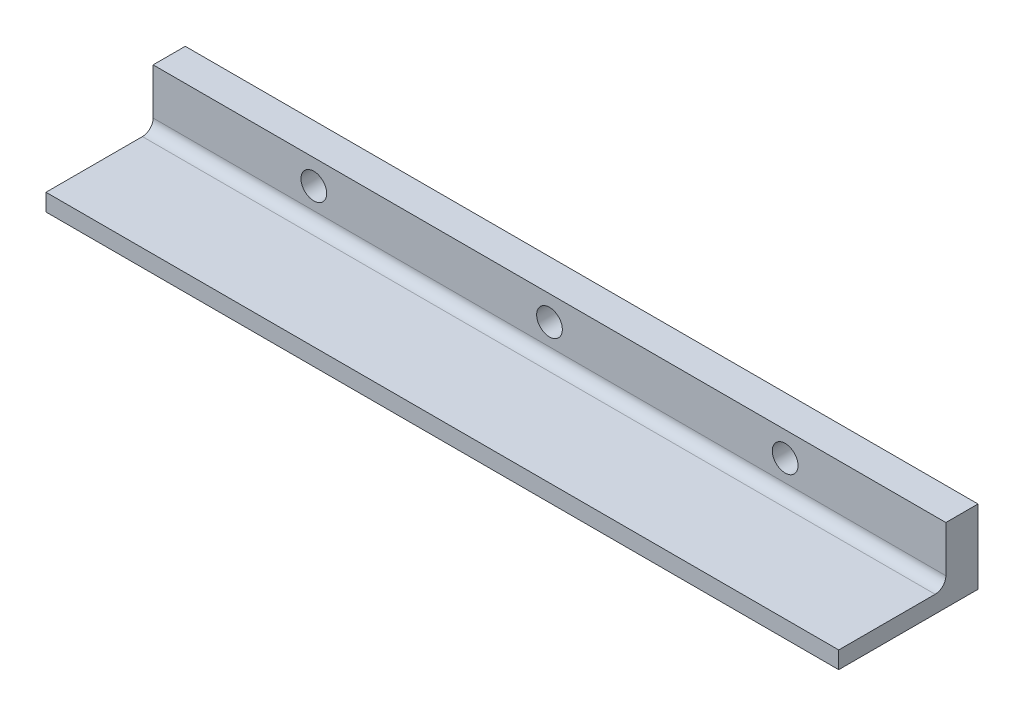
SolidWorks part; units mm, degrees
ref_plane "Front Plane" through (0, 0, 0) normal (0, 0, 1) x (1, 0, 0)
ref_plane "Top Plane" through (0, 0, 0) normal (0, 1, 0) x (1, 0, 0)
ref_plane "Right Plane" through (0, 0, 0) normal (1, 0, 0) x (0, 0, -1)
sketch "Sketch1" plane through (0, 0, 0) normal (0, 1, 0) x (1, 0, 0)
  line L1 (-37, -6.5) -> (37, -6.5)
  line L2 (-37, -6.5) -> (-37, 6.5)
  line L3 (-37, 6.5) -> (37, 6.5)
  line L4 (37, -6.5) -> (37, 6.5)
  line L5 (-37, -6.5) -> (37, 6.5) construction
  line L6 (-37, 6.5) -> (37, -6.5) construction
  point P0 (0, 0)
  dimension "D1" = 13
  dimension "D2" = 74
extrude "Boss-Extrude1" add sketch "Sketch1" along normal blind 1.6
sketch "Sketch2" plane through (0, 1.6, 0) normal (0, 1, 0) x (1, 0, 0)
  line L0 (37, -6.5) -> (37, 6.5) construction
  line L1 (-37, 6.5) -> (37, 6.5)
  line L2 (-37, 6.5) -> (-37, 3.5)
  line L3 (-37, 3.5) -> (37, 3.5)
  line L4 (37, 6.5) -> (37, 3.5)
  point P7 (39, -1.0619)
  dimension "D1" = 3
extrude "Boss-Extrude2" add sketch "Sketch2" along normal blind 5.3
fillet "Fillet1" radius 1 1 edges at (0, 1.6, -3.5)
sketch "Sketch3" plane through (0, 0, -6.5) normal (0, 0, 1) x (1, 0, 0)
  line L0 (0, 0) -> (0, 4.6) construction
  line L1 (22, 4.6) -> (-22, 4.6) construction
  point P6 (0, 4.6)
  dimension "D1" = 4.6
  dimension "D2" = 44
hole_wizard "M2 Clearance Hole1" positions "3DSketch1" profile "Sketch4" hole size "M2" standard "ANSI Metric" end condition through all
sketch3d "3DSketch1"
  point P0 (-22, 4.6, -6.5)
  point P3 (0, 4.6, -6.5)
  point P6 (22, 4.6, -6.5)
sketch "Sketch4" plane through (-22, 4.6, -6.5) normal (1, 0, 0) x (0, 1, 0)
  line L0 (0, 0) -> (0, 13)
  line L1 (0, 13) -> (1.2, 13)
  line L2 (1.2, 13) -> (1.2, 0)
  line L5 (1.2, 0) -> (0, 0)
  line L11 (0, -6.35) -> (0, 107.95) construction
  dimension "Thru Hole Dia." = 2.4
  dimension "Thru Hole Depth" = 13
